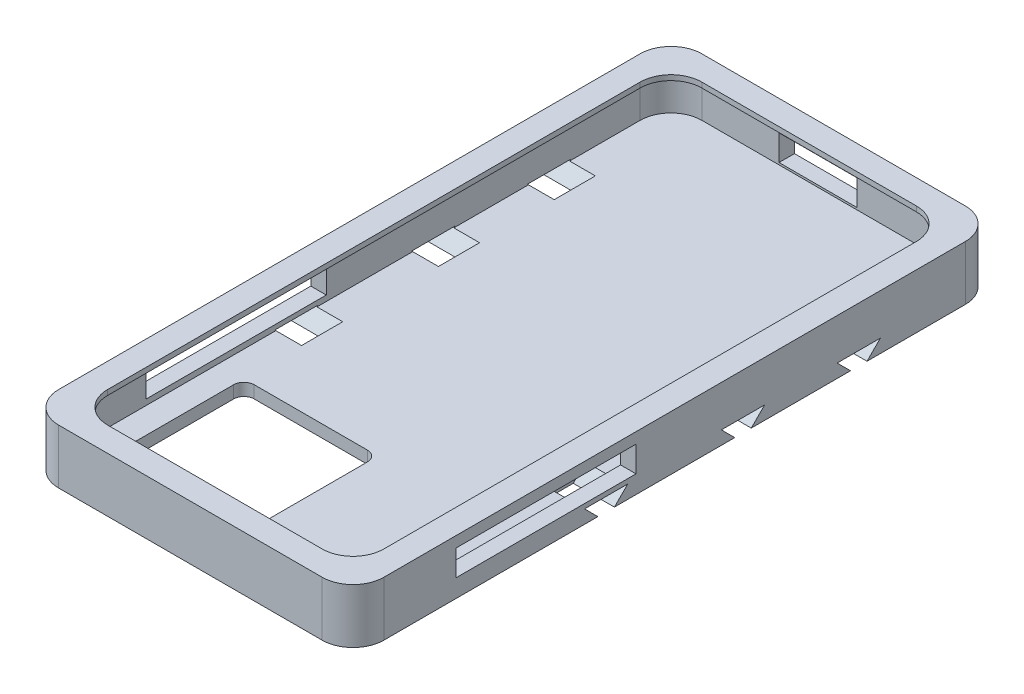
SolidWorks part; units mm, degrees
ref_plane "Front Plane" through (0, 0, 0) normal (0, 0, 1) x (1, 0, 0)
ref_plane "Top Plane" through (0, 0, 0) normal (0, 1, 0) x (1, 0, 0)
ref_plane "Right Plane" through (0, 0, 0) normal (1, 0, 0) x (0, 0, -1)
sketch "Sketch1" plane through (0, 0, 0) normal (0, 1, 0) x (1, 0, 0)
  line L1 (0, 0) -> (80.264, 0)
  line L2 (0, 0) -> (0, -158.75)
  line L3 (0, -158.75) -> (80.264, -158.75)
  line L4 (80.264, 0) -> (80.264, -158.75)
  dimension "D1" = 158.75
  dimension "D2" = 80.264
extrude "Boss-Extrude1" add sketch "Sketch1" along normal blind 3.048
sketch "Sketch2" plane through (0, 3.048, 0) normal (0, 1, 0) x (1, 0, 0)
  line L0 (80.264, 0) -> (0, 0) construction
  line L1 (11.43, -3.81) -> (68.834, -3.81)
  line L2 (3.81, -11.43) -> (3.81, -147.32)
  line L3 (11.43, -154.94) -> (68.834, -154.94)
  line L4 (76.454, -11.43) -> (76.454, -147.32)
  line L5 (0, -158.75) -> (80.264, -158.75) construction
  line L6 (80.264, -158.75) -> (80.264, 0) construction
  line L7 (0, 0) -> (0, -158.75) construction
  line L9 (0, 0) -> (80.264, 0)
  line L10 (0, 0) -> (0, -158.75)
  line L11 (0, -158.75) -> (80.264, -158.75)
  line L12 (80.264, 0) -> (80.264, -158.75)
  arc A0 (68.834, -154.94) -> (76.454, -147.32) centre (68.834, -147.32) ccw
  arc A1 (68.834, -3.81) -> (76.454, -11.43) centre (68.834, -11.43) cw
  arc A2 (11.43, -3.81) -> (3.81, -11.43) centre (11.43, -11.43) ccw
  arc A3 (3.81, -147.32) -> (11.43, -154.94) centre (11.43, -147.32) ccw
  dimension "D5" = 7.62
  dimension "D1" = 3.81
  dimension "D2" = 3.81
  dimension "D3" = 3.81
  dimension "D4" = 3.81
extrude "Boss-Extrude2" add sketch "Sketch2" along normal blind 10.414
fillet "Fillet2" radius 7.62 4 edges at (0, 6.731, 0) (80.264, 6.731, 0) (0, 6.731, 158.75) (80.264, 6.731, 158.75)
sketch "Sketch3" plane through (0, 13.462, 0) normal (0, 1, 0) x (1, 0, 0)
  line L0 (68.834, -3.81) -> (11.43, -3.81) construction
  line L1 (13.6618, -6.0418) -> (66.6022, -6.0418)
  line L2 (6.0418, -13.6618) -> (6.0418, -145.0882)
  line L3 (13.6618, -152.7082) -> (66.6022, -152.7082)
  line L4 (74.2222, -13.6618) -> (74.2222, -145.0882)
  line L5 (11.43, -3.81) -> (68.834, -3.81)
  line L6 (3.81, -11.43) -> (3.81, -147.32)
  line L7 (11.43, -154.94) -> (68.834, -154.94)
  line L8 (76.454, -11.43) -> (76.454, -147.32)
  line L9 (11.43, -154.94) -> (68.834, -154.94) construction
  line L10 (3.81, -11.43) -> (3.81, -147.32) construction
  line L11 (76.454, -147.32) -> (76.454, -11.43) construction
  arc A0 (11.43, -3.81) -> (3.81, -11.43) centre (11.43, -11.43) ccw construction
  arc A1 (68.834, -154.94) -> (76.454, -147.32) centre (68.834, -147.32) ccw construction
  arc A2 (66.6022, -6.0418) -> (74.2222, -13.6618) centre (66.6022, -13.6618) cw
  arc A3 (66.6022, -152.7082) -> (74.2222, -145.0882) centre (66.6022, -145.0882) ccw
  arc A4 (6.0418, -145.0882) -> (13.6618, -152.7082) centre (13.6618, -145.0882) ccw
  arc A5 (13.6618, -6.0418) -> (6.0418, -13.6618) centre (13.6618, -13.6618) ccw
  arc A6 (11.43, -3.81) -> (3.81, -11.43) centre (11.43, -11.43) ccw
  arc A7 (68.834, -3.81) -> (76.454, -11.43) centre (68.834, -11.43) cw
  arc A8 (68.834, -154.94) -> (76.454, -147.32) centre (68.834, -147.32) ccw
  arc A9 (3.81, -147.32) -> (11.43, -154.94) centre (11.43, -147.32) ccw
  point P14 (74.2222, -152.7082)
  point P19 (6.0418, -6.0418)
  point P34 (3.81, -3.81)
  point P39 (76.454, -154.94)
  dimension "D1" = 7.62
  dimension "D2" = 7.62
extrude "Boss-Extrude3" add sketch "Sketch3" against normal blind 1.27
sketch "Sketch4" plane through (0, 0, 0) normal (0, -1, 0) x (1, 0, 0)
  line L0 (0, 7.62) -> (0, 151.13) construction
  line L1 (12.7, 148.59) -> (40.64, 148.59)
  line L2 (10.16, 146.05) -> (10.16, 118.11)
  line L3 (12.7, 115.57) -> (40.64, 115.57)
  line L4 (43.18, 146.05) -> (43.18, 118.11)
  line L5 (7.62, 158.75) -> (72.644, 158.75) construction
  arc A0 (40.64, 115.57) -> (43.18, 118.11) centre (40.64, 118.11) ccw
  arc A1 (40.64, 148.59) -> (43.18, 146.05) centre (40.64, 146.05) cw
  arc A2 (12.7, 148.59) -> (10.16, 146.05) centre (12.7, 146.05) ccw
  arc A3 (10.16, 118.11) -> (12.7, 115.57) centre (12.7, 118.11) ccw
  point P10 (43.18, 115.57)
  point P13 (43.18, 148.59)
  point P18 (10.16, 115.57)
  dimension "D5" = 2.54
  dimension "D1" = 10.16
  dimension "D2" = 10.16
  dimension "D3" = 33.02
  dimension "D4" = 33.02
extrude "Cut-Extrude1" cut sketch "Sketch4" against normal through all
sketch "Sketch5" plane through (80.264, 0, 0) normal (1, 0, 0) x (0, 0, -1)
  line L0 (-98.298, 0) -> (-101.6, 3.302)
  line L1 (-151.13, 0) -> (-7.62, 0) construction
  line L2 (-101.6, 3.302) -> (-90.932, 3.302)
  line L3 (-90.932, 3.302) -> (-94.234, 0)
  line L4 (-98.298, 0) -> (-94.234, 0)
  line L5 (-158.75, 0) -> (-158.75, 13.462) construction
  line L6 (-60.452, 0) -> (-57.15, 3.302)
  line L7 (-57.15, 3.302) -> (-67.818, 3.302)
  line L8 (-67.818, 3.302) -> (-64.516, 0)
  line L9 (-64.516, 0) -> (-60.452, 0)
  line L10 (0, 13.462) -> (0, 0) construction
  line L11 (-39.243, 3.302) -> (-35.941, 0)
  line L12 (-35.941, 0) -> (-31.877, 0)
  line L13 (-31.877, 0) -> (-28.575, 3.302)
  line L14 (-39.243, 3.302) -> (-28.575, 3.302)
  dimension "D1" = 10.668
  dimension "D2" = 45
  dimension "D3" = 57.15
  dimension "D4" = 10.668
  dimension "D5" = 45
  dimension "D6" = 3.302
  dimension "D7" = 3.302
  dimension "D8" = 57.15
  dimension "D9" = 10.668
  dimension "D10" = 28.575
  dimension "D11" = 45
  dimension "D12" = 45
  dimension "D13" = 3.302
extrude "Cut-Extrude2" cut sketch "Sketch5" against normal blind 10.16
ref_plane "Plane1" through (40.132, 0, 0) normal (1, 0, 0) x (0, 0, -1)
mirror "Mirror1" about plane through (40.132, 0, 0) normal (1, 0, 0) of "Cut-Extrude2"
sketch "Sketch6" plane through (0, 0, 0) normal (0, 0, -1) x (-1, 0, 0)
  line L0 (-49.784, 9.906) -> (-30.48, 9.906)
  line L5 (-30.48, 3.556) -> (-49.784, 3.556)
  line L6 (0, 13.462) -> (0, 0) construction
  line L7 (-49.784, 9.906) -> (-49.784, 3.556)
  line L8 (-30.48, 9.906) -> (-30.48, 3.556)
  line L9 (-80.264, 0) -> (-80.264, 13.462) construction
  line L10 (0, 13.462) -> (-7.62, 13.462) construction
  dimension "D1" = 6.35
  dimension "D2" = 30.48
  dimension "D3" = 30.48
  dimension "D4" = 3.556
extrude "Cut-Extrude4" cut sketch "Sketch6" against normal up to surface (3.81 mm away) up to face at (40.132, 7.62, 3.81)
sketch "Sketch7" plane through (0, 0, 0) normal (-1, 0, 0) x (0, 0, 1)
  line L0 (158.75, 13.462) -> (158.75, 0) construction
  line L1 (88.9, 10.795) -> (133.35, 10.795)
  line L2 (88.9, 10.795) -> (88.9, 4.445)
  line L3 (88.9, 4.445) -> (133.35, 4.445)
  line L4 (133.35, 10.795) -> (133.35, 4.445)
  line L6 (98.298, 0) -> (151.13, 0) construction
  dimension "D1" = 25.4
  dimension "D2" = 44.45
  dimension "D3" = 6.35
  dimension "D4" = 4.445
extrude "Cut-Extrude5" cut sketch "Sketch7" against normal through all
